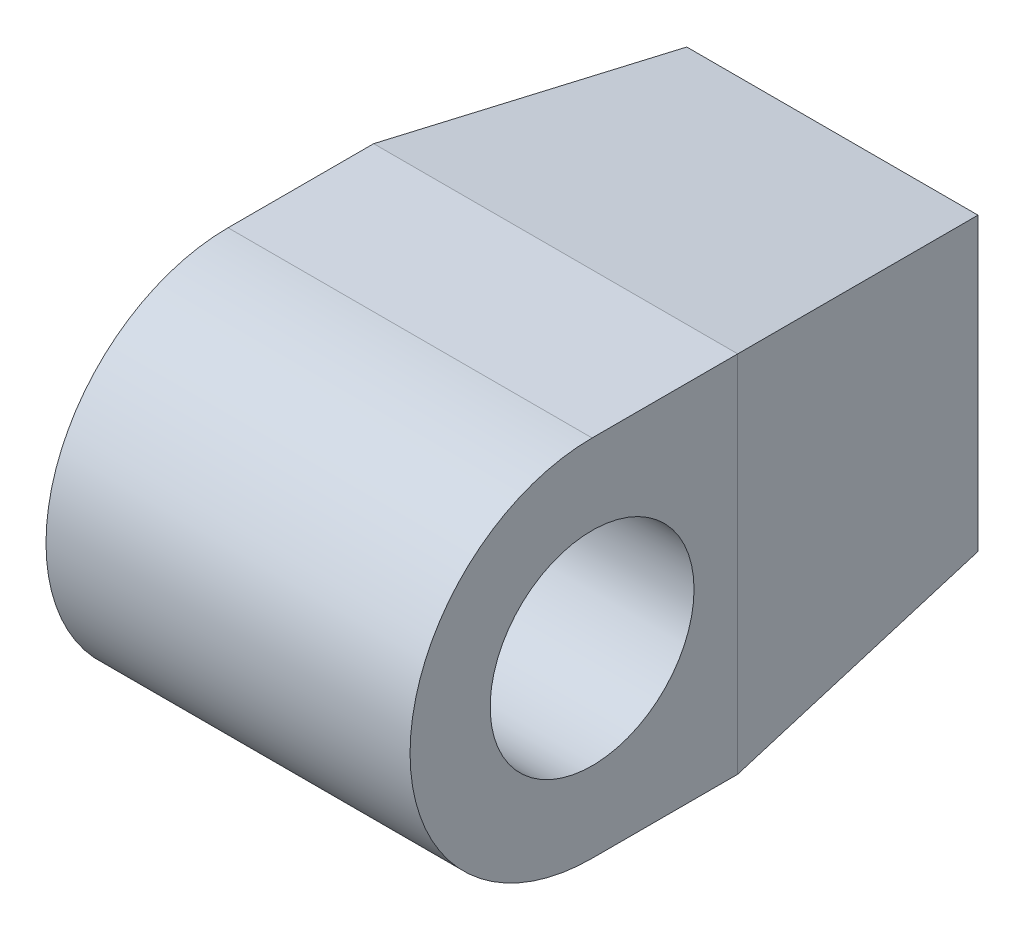
SolidWorks part; units mm, degrees
material "Maraging"
ref_plane "Front Plane" through (0, 0, 0) normal (0, 0, 1) x (1, 0, 0)
ref_plane "Top Plane" through (0, 0, 0) normal (0, 1, 0) x (1, 0, 0)
ref_plane "Right Plane" through (0, 0, 0) normal (1, 0, 0) x (0, 0, -1)
sketch "Sketch1" plane through (0, 0, 0) normal (0, 0, 1) x (1, 0, 0)
  line L1 (-10, -10) -> (10, -10)
  line L2 (-10, -10) -> (-10, 10)
  line L3 (-10, 10) -> (10, 10)
  line L4 (10, -10) -> (10, 10)
  line L5 (-10, -10) -> (10, 10) construction
  line L6 (-10, 10) -> (10, -10) construction
  circle A0 centre (0, 0) radius 10 construction
  dimension "D1" = 20
ref_plane "Plane1" through (0, 0, 19) normal (0, 0, 1) x (1, 0, 0)
sketch "Sketch2" plane through (0, 0, 19) normal (0, 0, 1) x (1, 0, 0)
  line L1 (-12.5, -12.5) -> (12.5, -12.5)
  line L2 (-12.5, -12.5) -> (-12.5, 12.5)
  line L3 (-12.5, 12.5) -> (12.5, 12.5)
  line L4 (12.5, -12.5) -> (12.5, 12.5)
  line L5 (-12.5, -12.5) -> (12.5, 12.5) construction
  line L6 (-12.5, 12.5) -> (12.5, -12.5) construction
  point P0 (0, 0)
  dimension "D1" = 25
loft "Loft1" add profiles "Sketch2", "Sketch1"
sketch "Sketch3" plane through (0, 0, 0) normal (1, 0, 0) x (0, 0, -1)
  line L0 (-19, 12.5) -> (-29, 12.5)
  line L1 (-29, -12.5) -> (-19, -12.5)
  line L2 (-19, -12.5) -> (-19, 12.5)
  arc A0 (-29, 12.5) -> (-29, -12.5) centre (-29, 0) ccw
  dimension "D1" = 10
extrude "Boss-Extrude1" add sketch "Sketch3" along normal through all and the other way through all
sketch "Sketch4" plane through (12.5001, 0, 0) normal (1, 0, 0) x (0, 0, -1)
  circle A0 centre (-29, 0) radius 7
  arc A1 (-29, 12.5) -> (-29, -12.5) centre (-29, 0) ccw construction
  dimension "D1" = 14
extrude "Cut-Extrude1" cut sketch "Sketch4" against normal blind 10
hole_wizard "Ø8.0mm Dowel Hole1" positions "3DSketch2" profile "Sketch6" hole size "Ø8.0" standard "ISO"
sketch3d "3DSketch2"
  line L0 (10, 10, 0) -> (-10, 10, 0) construction
  line L1 (10, -10, 0) -> (10, 10, 0) construction
  point P0 (0, 0, 0)
  point P6 (0, 10, 0)
  point P9 (10, 0, 0)
sketch "Sketch6" plane through (0, 0, 0) normal (1, 0, 0) x (0, 1, 0)
  line L0 (0, 0) -> (0, 14.4034)
  line L1 (0, 14.4034) -> (4, 12)
  line L2 (4, 12) -> (4, 0.025)
  line L3 (4, 0.025) -> (4.025, 0)
  line L5 (4.025, 0) -> (0, 0)
  line L6 (-4, 0.025) -> (-4.025, 0) construction
  line L10 (0, 14.4034) -> (-4, 12) construction
  line L11 (0, -6.35) -> (0, 107.95) construction
  dimension "Hole Dia." = 8
  dimension "Hole Depth" = 12
  dimension "Near C'Sink Dia." = 8.05
  dimension "Near C'Sink Angle" = 90
  dimension "Drill Angle" = 118
